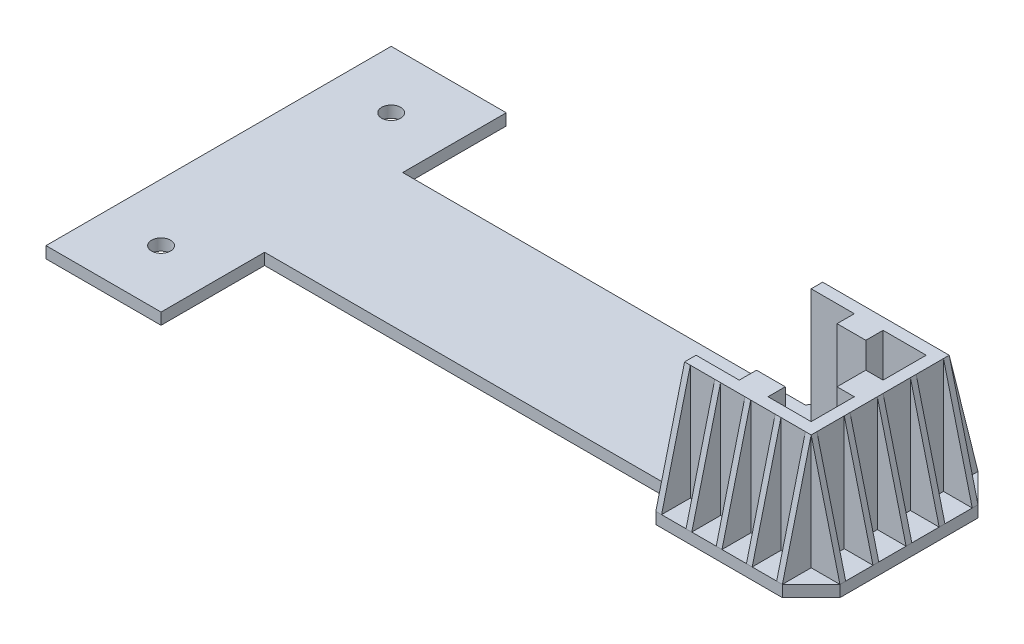
SolidWorks part; units mm, degrees
ref_plane "Front Plane" through (0, 0, 0) normal (0, 0, 1) x (1, 0, 0)
ref_plane "Top Plane" through (0, 0, 0) normal (0, 1, 0) x (1, 0, 0)
ref_plane "Right Plane" through (0, 0, 0) normal (1, 0, 0) x (0, 0, -1)
sketch "Sketch1" plane through (0, 0, 0) normal (0, 1, 0) x (1, 0, 0)
  line L0 (20, 18) -> (115, 18)
  line L1 (0, 0) -> (20, 0)
  line L2 (0, 0) -> (0, 60)
  line L3 (0, 60) -> (20, 60)
  line L4 (20, 0) -> (20, 18)
  line L5 (115, 18) -> (115, 42)
  line L6 (115, 42) -> (20, 42)
  line L7 (20, 42) -> (20, 60)
  line L8 (10, 0) -> (10, 10) construction
  line L9 (103, 30) -> (115, 30) construction
  circle A0 centre (10, 10) radius 1.65
  circle A1 centre (10, 50) radius 1.65
  circle A2 centre (103, 30) radius 2.5
  dimension "D6" = 3.3
  dimension "D8" = 3.3
  dimension "D10" = 5
  dimension "D11" = 12
  dimension "D1" = 20
  dimension "D2" = 60
  dimension "D3" = 24
  dimension "D4" = 18
  dimension "D5" = 115
  dimension "D7" = 10
  dimension "D9" = 10
extrude "Boss-Extrude1" add sketch "Sketch1" along normal blind 2
sketch "Sketch2" plane through (0, 2, 0) normal (0, 1, 0) x (1, 0, 0)
  line L0 (20, 18) -> (115, 18) construction
  line L1 (115, 42) -> (93, 42)
  line L2 (115, 42) -> (115, 18)
  line L3 (115, 18) -> (93, 18)
  line L4 (93, 42) -> (93, 40)
  line L5 (93, 40) -> (100.5, 40)
  line L6 (113, 40) -> (113, 32.5)
  line L7 (113, 20) -> (105.5, 20)
  line L8 (93, 20) -> (93, 18)
  line L9 (100.5, 40) -> (100.5, 37)
  line L10 (105.5, 40) -> (105.5, 37)
  line L11 (113, 27.5) -> (110, 27.5)
  line L12 (110, 27.5) -> (110, 32.5)
  line L13 (110, 32.5) -> (113, 32.5)
  line L14 (100.5, 37) -> (105.5, 37)
  line L15 (100.5, 23) -> (105.5, 23)
  line L16 (100.5, 23) -> (100.5, 20)
  line L17 (105.5, 23) -> (105.5, 20)
  line L18 (105.5, 40) -> (113, 40)
  line L19 (113, 27.5) -> (113, 20)
  line L20 (100.5, 20) -> (93, 20)
  dimension "D1" = 22
  dimension "D2" = 2
  dimension "D3" = 2
  dimension "D4" = 2
  dimension "D5" = 7.5
  dimension "D6" = 5
  dimension "D7" = 3
  dimension "D8" = 7.5
  dimension "D9" = 5
  dimension "D10" = 3
  dimension "D11" = 3
extrude "Boss-Extrude2" add sketch "Sketch2" along normal blind 20
sketch "Sketch4" plane through (0, 0, 0) normal (0, 1, 0) x (1, 0, 0)
  line L0 (98.25, 18) -> (99.25, 18)
  line L1 (93, 18) -> (94, 18)
  line L2 (93, 18) -> (93, 13)
  line L3 (93, 13) -> (94, 13)
  line L4 (94, 18) -> (94, 13)
  line L5 (98.25, 18) -> (98.25, 13)
  line L6 (98.25, 13) -> (99.25, 13)
  line L7 (99.25, 18) -> (99.25, 13)
  line L8 (103.5, 18) -> (104.5, 18)
  line L9 (103.5, 18) -> (103.5, 13)
  line L10 (103.5, 13) -> (104.5, 13)
  line L11 (104.5, 18) -> (104.5, 13)
  line L12 (108.75, 18) -> (109.75, 18)
  line L13 (108.75, 18) -> (108.75, 13)
  line L14 (108.75, 13) -> (109.75, 13)
  line L15 (109.75, 18) -> (109.75, 13)
  line L16 (114, 18) -> (115, 18)
  line L17 (114, 18) -> (114, 13)
  line L18 (114, 13) -> (115, 13)
  line L19 (115, 18) -> (115, 13)
  line L20 (115, 18) -> (115, 42) construction
  line L21 (103, 30) -> (50103, 30) construction
  line L22 (115, 42) -> (115, 47)
  line L23 (114, 47) -> (115, 47)
  line L24 (114, 42) -> (114, 47)
  line L25 (114, 42) -> (115, 42)
  line L26 (109.75, 42) -> (109.75, 47)
  line L27 (108.75, 47) -> (109.75, 47)
  line L28 (108.75, 42) -> (108.75, 47)
  line L29 (108.75, 42) -> (109.75, 42)
  line L30 (104.5, 42) -> (104.5, 47)
  line L31 (103.5, 47) -> (104.5, 47)
  line L32 (103.5, 42) -> (103.5, 47)
  line L33 (103.5, 42) -> (104.5, 42)
  line L34 (99.25, 42) -> (99.25, 47)
  line L35 (98.25, 47) -> (99.25, 47)
  line L36 (98.25, 42) -> (98.25, 47)
  line L37 (94, 42) -> (94, 47)
  line L38 (93, 47) -> (94, 47)
  line L39 (93, 42) -> (93, 47)
  line L40 (93, 42) -> (94, 42)
  line L41 (98.25, 42) -> (99.25, 42)
  dimension "D1" = 5
  dimension "D2" = 1
  dimension "D3" = 5
extrude "Boss-Extrude3" add sketch "Sketch4" along normal up to surface (22 mm away) up to face at (104.9, 22, -30)
sketch "Sketch5" plane through (0, 0, 0) normal (0, 1, 0) x (1, 0, 0)
  line L0 (115, 13) -> (115, 47) construction
  line L1 (115, 18) -> (120, 18)
  line L2 (115, 18) -> (115, 19)
  line L3 (115, 19) -> (120, 19)
  line L4 (120, 18) -> (120, 19)
  line L5 (109.75, 18) -> (114, 18) construction
  line L6 (115, 23.75) -> (120, 23.75)
  line L7 (115, 23.75) -> (115, 24.75)
  line L8 (115, 24.75) -> (120, 24.75)
  line L9 (120, 23.75) -> (120, 24.75)
  line L10 (115, 29.5) -> (120, 29.5)
  line L11 (115, 29.5) -> (115, 30.5)
  line L12 (115, 30.5) -> (120, 30.5)
  line L13 (120, 29.5) -> (120, 30.5)
  line L14 (115, 35.25) -> (120, 35.25)
  line L15 (115, 35.25) -> (115, 36.25)
  line L16 (115, 36.25) -> (120, 36.25)
  line L17 (120, 35.25) -> (120, 36.25)
  line L18 (115, 41) -> (120, 41)
  line L19 (115, 41) -> (115, 42)
  line L20 (115, 42) -> (120, 42)
  line L21 (120, 41) -> (120, 42)
  line L22 (114, 42) -> (109.75, 42) construction
  dimension "D1" = 5
  dimension "D2" = 1
  dimension "D3" = 5
extrude "Boss-Extrude4" add sketch "Sketch5" along normal up to surface (22 mm away) up to face at (104.3462, 22, -30)
sketch "Sketch6" plane through (0, 0, 0) normal (0, 1, 0) x (1, 0, 0)
  line L0 (90, 42) -> (115, 42)
  line L1 (93, 42) -> (20, 42) construction
  line L2 (115, 42) -> (115, 18)
  line L3 (115, 18) -> (90, 18)
  line L4 (20, 18) -> (93, 18) construction
  line L5 (90, 18) -> (93, 13)
  line L6 (93, 13) -> (115, 13)
  line L7 (115, 13) -> (120, 18)
  line L8 (120, 18) -> (120, 42)
  line L9 (120, 42) -> (115, 47)
  line L10 (115, 47) -> (93, 47)
  line L11 (93, 47) -> (90, 42)
  dimension "D1" = 25
extrude "Boss-Extrude5" add sketch "Sketch6" along normal up to surface (2 mm away) up to face at (103, 2, -27.5)
chamfer "Chamfer1" distance 5 distance2 20 15 edges at (93.5, 22, -47) (98.75, 22, -47) (104, 22, -47) (109.25, 22, -47) (120, 22, -41.5) (120, 22, -35.75) (120, 22, -30) (120, 22, -18.5) (114.5, 22, -13) (109.25, 22, -13) (104, 22, -13) (98.75, 22, -13) (114.5, 22, -47) (120, 22, -24.25) (93.5, 22, -13)
